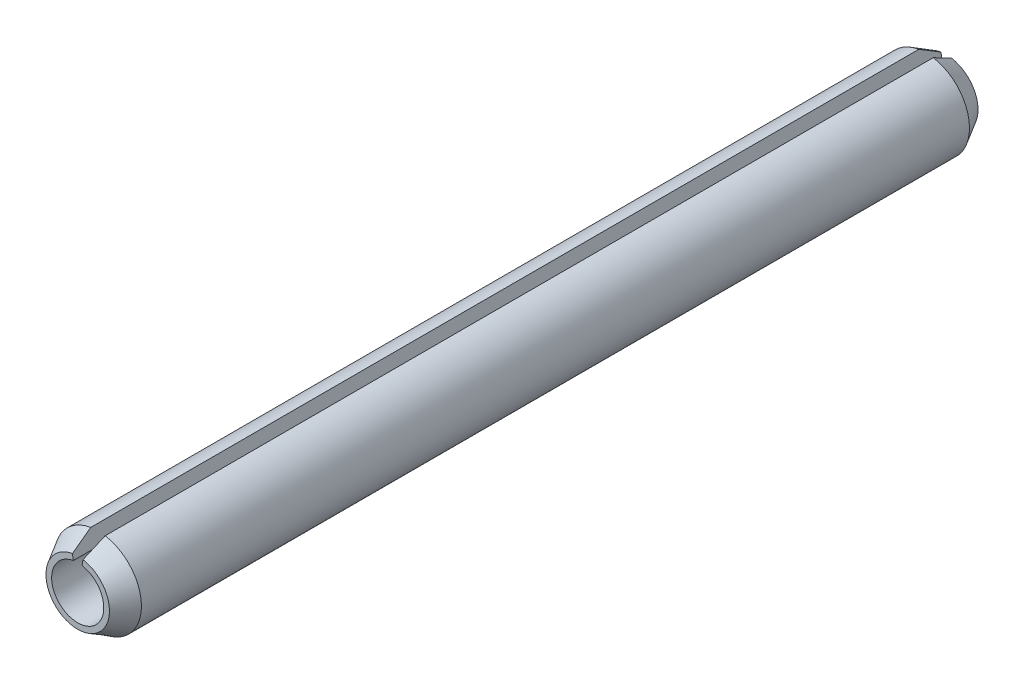
SolidWorks part; units mm, degrees
material "Plain Carbon Steel"
ref_plane "Front" through (0, 0, 0) normal (0, 0, 1) x (1, 0, 0)
ref_plane "Base" through (0, 0, 0) normal (0, 1, 0) x (1, 0, 0)
ref_plane "Side" through (0, 0, 0) normal (1, 0, 0) x (0, 0, -1)
sketch "Sketch1" plane through (0, 0, 0) normal (0, 0, 1) x (1, 0, 0)
  line L2 (0, 0) -> (0, 3) construction
  arc A0 (-0.5, 2.958) -> (0.5, 2.958) centre (0, 0) ccw
  dimension "NOMDIA" = 6
  dimension "D1" = 1
extrude "Base-Extrude-Thin" add sketch "Sketch1" along normal mid plane 60 thin thin type one direction reverse wall 1.2
chamfer "Chamfer1" distance 1.4 angle 30 2 edges at (0, -3, 30) (0, -3, -30)
equation "\"D1@Sketch1\"=\"NOMDIA@Sketch1\"/6"
